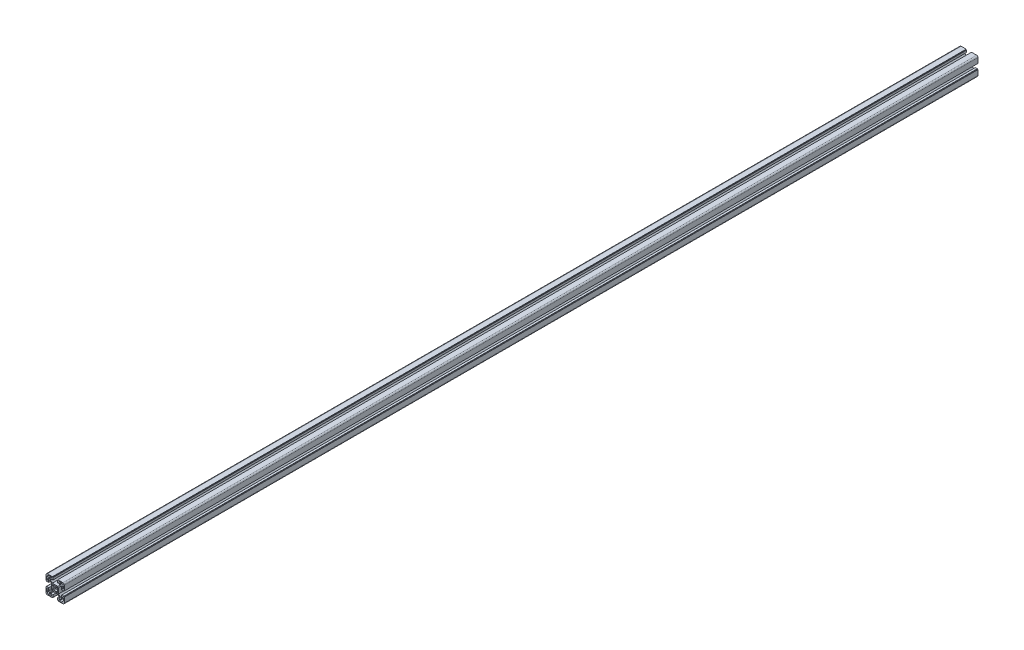
SolidWorks part; units mm, degrees
material "6061 Alloy"
ref_plane "Front Plane" through (0, 0, 0) normal (0, 0, 1) x (1, 0, 0)
ref_plane "Top Plane" through (0, 0, 0) normal (0, 1, 0) x (1, 0, 0)
ref_plane "Right Plane" through (0, 0, 0) normal (1, 0, 0) x (0, 0, -1)
sketch "Sketch1" plane through (0, 0, 0) normal (0, 0, 1) x (1, 0, 0)
  line L0 (5.8, -20) -> (17, -20)
  line L1 (14, -10.05) -> (11.4642, -10.05)
  line L2 (0, -21.1722) -> (0, 18.817) construction
  line L3 (0, 21.1722) -> (0, -18.817) construction
  line L4 (14.5, -18.5) -> (9.5, -18.5)
  line L5 (18.5, 5) -> (14, 5)
  line L6 (6.0858, -7.5) -> (10.05, -11.4642)
  line L7 (20, 5.8) -> (18.5, 5.8)
  line L8 (14, 5) -> (14, 10.05)
  line L9 (18.5, 5.8) -> (18.5, 5)
  line L10 (18.5, 14.5) -> (17.25, 14.5)
  line L11 (14.5, 11.75) -> (15.5, 11.75)
  line L12 (14.5, 17.25) -> (14.5, 18.5)
  line L13 (18.5, 9.5) -> (18.5, 14.5)
  line L14 (15.5, 11.75) -> (15.5, 9.5)
  line L15 (20, 17) -> (20, 5.8)
  line L16 (5.5, 5.5) -> (2.3979, 5.5)
  line L17 (2.3979, 5.5) -> (1.9983, 4.5833)
  line L18 (5.5, 2.3979) -> (5.5, 5.5)
  line L19 (4.5833, 1.9983) -> (5.5, 2.3979)
  line L20 (5, -14) -> (5, -18.5)
  line L21 (11.4642, 10.05) -> (7.5, 6.0858)
  line L22 (-6.0858, 7.5) -> (6.0858, 7.5)
  line L23 (11.75, 15.5) -> (11.75, 14.5)
  line L24 (5, -18.5) -> (5.8, -18.5)
  line L25 (5.8, -18.5) -> (5.8, -20)
  line L26 (10.05, -11.4642) -> (10.05, -14)
  line L27 (10.05, -14) -> (5, -14)
  line L28 (9.5, -15.5) -> (11.75, -15.5)
  line L29 (11.75, -15.5) -> (11.75, -14.5)
  line L30 (9.5, 15.5) -> (11.75, 15.5)
  line L31 (10.05, 14) -> (5, 14)
  line L32 (10.05, 11.4642) -> (10.05, 14)
  line L33 (5.8, 18.5) -> (5.8, 20)
  line L34 (5, 18.5) -> (5.8, 18.5)
  line L35 (7.5, -6.0858) -> (7.5, 6.0858)
  line L36 (5, 14) -> (5, 18.5)
  line L37 (6.0858, 7.5) -> (10.05, 11.4642)
  line L38 (14.5, 18.5) -> (9.5, 18.5)
  line L39 (14, 10.05) -> (11.4642, 10.05)
  line L40 (5.8, 20) -> (17, 20)
  line L41 (-18.5, -5) -> (-14, -5)
  line L42 (-6.0858, -7.5) -> (6.0858, -7.5)
  line L43 (11.4642, -10.05) -> (7.5, -6.0858)
  line L44 (-20, -5.8) -> (-18.5, -5.8)
  line L45 (-14, -5) -> (-14, -10.05)
  line L46 (-18.5, -5.8) -> (-18.5, -5)
  line L47 (-18.5, -14.5) -> (-17.25, -14.5)
  line L48 (4.5833, -1.9983) -> (5.5, -2.3979)
  line L49 (5.5, -2.3979) -> (5.5, -5.5)
  line L50 (2.3979, -5.5) -> (1.9983, -4.5833)
  line L51 (5.5, -5.5) -> (2.3979, -5.5)
  line L52 (-14.5, -11.75) -> (-15.5, -11.75)
  line L53 (-14.5, -17.25) -> (-14.5, -18.5)
  line L54 (-18.5, -9.5) -> (-18.5, -14.5)
  line L55 (-15.5, -11.75) -> (-15.5, -9.5)
  line L56 (-20, -17) -> (-20, -5.8)
  line L57 (-5.5, -5.5) -> (-2.3979, -5.5)
  line L58 (-2.3979, -5.5) -> (-1.9983, -4.5833)
  line L59 (-5.5, -2.3979) -> (-5.5, -5.5)
  line L60 (-4.5833, -1.9983) -> (-5.5, -2.3979)
  line L61 (-11.4642, -10.05) -> (-7.5, -6.0858)
  line L62 (-5.8, 20) -> (-17, 20)
  line L63 (-14, 10.05) -> (-11.4642, 10.05)
  line L64 (-14.5, 18.5) -> (-9.5, 18.5)
  line L65 (-6.0858, 7.5) -> (-10.05, 11.4642)
  line L66 (-5, 14) -> (-5, 18.5)
  line L67 (-7.5, -6.0858) -> (-7.5, 6.0858)
  line L68 (-5, 18.5) -> (-5.8, 18.5)
  line L69 (-5.8, 18.5) -> (-5.8, 20)
  line L70 (-10.05, 11.4642) -> (-10.05, 14)
  line L71 (-10.05, 14) -> (-5, 14)
  line L72 (-9.5, 15.5) -> (-11.75, 15.5)
  line L73 (-11.75, -15.5) -> (-11.75, -14.5)
  line L74 (-9.5, -15.5) -> (-11.75, -15.5)
  line L75 (-10.05, -14) -> (-5, -14)
  line L76 (-10.05, -11.4642) -> (-10.05, -14)
  line L77 (-5.8, -18.5) -> (-5.8, -20)
  line L78 (-5, -18.5) -> (-5.8, -18.5)
  line L79 (-11.75, 15.5) -> (-11.75, 14.5)
  line L80 (-11.4642, 10.05) -> (-7.5, 6.0858)
  line L81 (-5, -14) -> (-5, -18.5)
  line L82 (-4.5833, 1.9983) -> (-5.5, 2.3979)
  line L83 (-5.5, 2.3979) -> (-5.5, 5.5)
  line L84 (-2.3979, 5.5) -> (-1.9983, 4.5833)
  line L85 (-5.5, 5.5) -> (-2.3979, 5.5)
  line L86 (-20, 17) -> (-20, 5.8)
  line L87 (-15.5, 11.75) -> (-15.5, 9.5)
  line L88 (20, -17) -> (20, -5.8)
  line L89 (15.5, -11.75) -> (15.5, -9.5)
  line L90 (18.5, -9.5) -> (18.5, -14.5)
  line L91 (14.5, -17.25) -> (14.5, -18.5)
  line L92 (14.5, -11.75) -> (15.5, -11.75)
  line L93 (18.5, -14.5) -> (17.25, -14.5)
  line L94 (-18.5, 9.5) -> (-18.5, 14.5)
  line L95 (-14.5, 17.25) -> (-14.5, 18.5)
  line L96 (18.5, -5.8) -> (18.5, -5)
  line L97 (14, -5) -> (14, -10.05)
  line L98 (20, -5.8) -> (18.5, -5.8)
  line L99 (18.5, -5) -> (14, -5)
  line L100 (-14.5, 11.75) -> (-15.5, 11.75)
  line L101 (-18.5, 14.5) -> (-17.25, 14.5)
  line L102 (-18.5, 5.8) -> (-18.5, 5)
  line L103 (-14, 5) -> (-14, 10.05)
  line L104 (-20, 5.8) -> (-18.5, 5.8)
  line L105 (-6.0858, -7.5) -> (-10.05, -11.4642)
  line L106 (-18.5, 5) -> (-14, 5)
  line L107 (-14.5, -18.5) -> (-9.5, -18.5)
  line L108 (-20, 0) -> (20.788, 0) construction
  line L109 (-14, -10.05) -> (-11.4642, -10.05)
  line L110 (-5.8, -20) -> (-17, -20)
  arc A0 (14.5, -11.75) -> (11.75, -14.5) centre (14.5, -14.5) ccw
  arc A1 (18.5, 9.5) -> (15.5, 9.5) centre (17, 9.5) cw
  arc A2 (14.5, 17.25) -> (17.25, 14.5) centre (14.5, 14.5) cw
  arc A3 (17, 20) -> (20, 17) centre (17, 17) cw
  arc A4 (-1.9983, 4.5833) -> (1.9983, 4.5833) centre (0, 0) cw
  arc A5 (9.5, 15.5) -> (9.5, 18.5) centre (9.5, 17) cw
  arc A6 (9.5, -15.5) -> (9.5, -18.5) centre (9.5, -17) ccw
  arc A7 (14.5, 11.75) -> (11.75, 14.5) centre (14.5, 14.5) cw
  arc A8 (4.5833, -1.9983) -> (4.5833, 1.9983) centre (0, 0) ccw
  arc A9 (-18.5, -9.5) -> (-15.5, -9.5) centre (-17, -9.5) cw
  arc A10 (-14.5, -17.25) -> (-17.25, -14.5) centre (-14.5, -14.5) cw
  arc A11 (-1.9983, -4.5833) -> (1.9983, -4.5833) centre (0, 0) ccw
  arc A12 (-17, -20) -> (-20, -17) centre (-17, -17) cw
  arc A13 (-4.5833, -1.9983) -> (-4.5833, 1.9983) centre (0, 0) cw
  arc A14 (-14.5, 11.75) -> (-11.75, 14.5) centre (-14.5, 14.5) ccw
  arc A15 (-9.5, -15.5) -> (-9.5, -18.5) centre (-9.5, -17) cw
  arc A16 (-9.5, 15.5) -> (-9.5, 18.5) centre (-9.5, 17) ccw
  arc A17 (-17, 20) -> (-20, 17) centre (-17, 17) ccw
  arc A18 (17, -20) -> (20, -17) centre (17, -17) ccw
  arc A19 (14.5, -17.25) -> (17.25, -14.5) centre (14.5, -14.5) ccw
  arc A20 (18.5, -9.5) -> (15.5, -9.5) centre (17, -9.5) ccw
  arc A21 (-14.5, 17.25) -> (-17.25, 14.5) centre (-14.5, 14.5) ccw
  arc A22 (-18.5, 9.5) -> (-15.5, 9.5) centre (-17, 9.5) ccw
  arc A23 (-14.5, -11.75) -> (-11.75, -14.5) centre (-14.5, -14.5) cw
  point P55 (7.5, 0)
  point P101 (-7.5, 0)
  point P116 (0, -7.5)
  point P149 (0, 7.5)
extrude "Extrude1" add sketch "Sketch1" along normal blind 2000
hole_wizard "M12 Tapped Hole1" [suppressed] positions "3DSketch2" profile "Sketch3" tap size "M12" standard "ISO"
sketch3d "3DSketch2"
  line L0 (-20, 17, 0) -> (-20, 5.8, 0) construction
  line L1 (-5.8, 20, 0) -> (-17, 20, 0) construction
  line L2 (-5.8, 20, 200) -> (-17, 20, 200) construction
  line L3 (-20, 17, 200) -> (-20, 5.8, 200) construction
  point P0 (0, 0, 200)
  point P2 (0, 0, 0)
  dimension "D1" = 20
  dimension "D2" = 20
  dimension "D3" = 20
  dimension "D4" = 20
sketch "Sketch3" plane through (0, 0, 200) normal (1, 0, 0) x (0, -1, 0)
  line L0 (0, 0) -> (0, 35.8144)
  line L1 (0, 35.8144) -> (5.1, 32.75)
  line L2 (5.1, 32.75) -> (5.1, 0.925)
  line L3 (5.1, 0.925) -> (6.025, 0)
  line L5 (6.025, 0) -> (0, 0)
  line L6 (-5.1, 0.925) -> (-6.025, 0) construction
  line L10 (0, 35.8144) -> (-5.1, 32.75) construction
  line L11 (0, -6.35) -> (0, 107.95) construction
  dimension "Tap Drill Dia." = 10.2
  dimension "Tap Drill Depth" = 32.75
  dimension "Near C'Sink Dia." = 12.05
  dimension "Near C'Sink Angle" = 90
  dimension "Drill Angle" = 118
cosmetic thread "Hole Thread1" [suppressed] parameters "D1"=24, "D2"=12
cosmetic thread "Filettatura del foro1" [suppressed] parameters "D1"=24, "D2"=12
hole_wizard "Ø9.8 (9.8) Diameter Hole1" [suppressed] positions "3DSketch3" profile "Sketch4" hole size "Ø9.8" standard "ISO"
sketch3d "3DSketch3"
  line L0 (-5.8, 20, 200) -> (-17, 20, 200) construction
  line L1 (20, -17, 200) -> (20, -5.8, 200) construction
  line L2 (17, 20, 0) -> (5.8, 20, 0) construction
  line L3 (20, -17, 0) -> (20, -5.8, 0) construction
  point P0 (0, 20, 184)
  point P2 (20, 0, 184)
  point P4 (0, 20, 16)
  point P6 (20, 0, 16)
  dimension "D1" = 16
  dimension "D2" = 20
  dimension "D3" = 20
  dimension "D4" = 16
  dimension "D5" = 16
  dimension "D6" = 16
sketch "Sketch4" plane through (0, 20, 184) normal (1, 0, 0) x (0, 0, 1)
  line L0 (0, 0) -> (0, 40)
  line L1 (0, 40) -> (4.9, 40)
  line L2 (4.9, 40) -> (4.9, 0)
  line L5 (4.9, 0) -> (0, 0)
  line L11 (0, -6.35) -> (0, 107.95) construction
  dimension "Thru Hole Dia." = 9.8
  dimension "Thru Hole Depth" = 40
hole_wizard "Ø17.0 (17) Diameter Hole1" [suppressed] positions "3DSketch4" profile "Sketch5" hole size "Ø17.0" standard "ISO"
sketch3d "3DSketch4"
  line L0 (-5.8, 20, 200) -> (-17, 20, 200) construction
  line L1 (-5.8, 20, 0) -> (-17, 20, 0) construction
  point P0 (0, 20, 177.5)
  point P2 (0, 20, 22.5)
  dimension "D1" = 20
  dimension "D2" = 22.5
  dimension "D3" = 22.5
sketch "Sketch5" plane through (0, 20, 177.5) normal (1, 0, 0) x (0, 0, 1)
  line L0 (0, 0) -> (0, 40)
  line L1 (0, 40) -> (8.5, 40)
  line L2 (8.5, 40) -> (8.5, 0)
  line L5 (8.5, 0) -> (0, 0)
  line L11 (0, -6.35) -> (0, 107.95) construction
  dimension "Thru Hole Dia." = 17
  dimension "Thru Hole Depth" = 40
